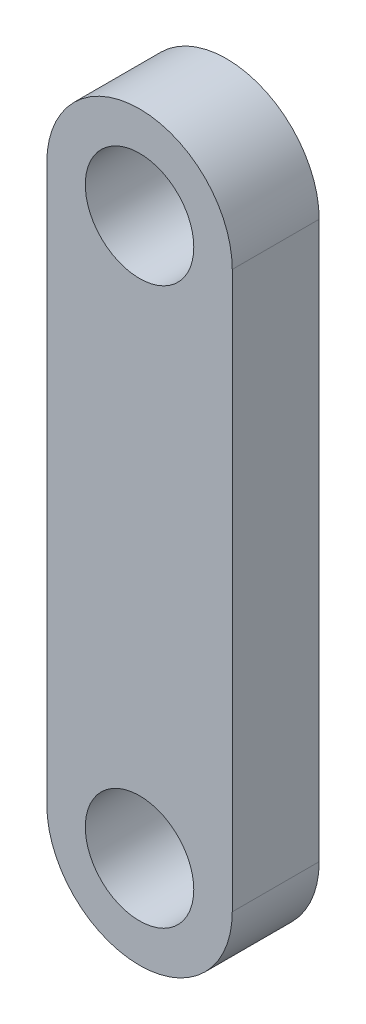
SolidWorks part; units mm, degrees
material "Titanium"
ref_plane "Front Plane" through (0, 0, 0) normal (0, 0, 1) x (1, 0, 0)
ref_plane "Top Plane" through (0, 0, 0) normal (0, 1, 0) x (1, 0, 0)
ref_plane "Right Plane" through (0, 0, 0) normal (1, 0, 0) x (0, 0, -1)
sketch "Sketch1" plane through (0, 0, 0) normal (0, 0, 1) x (1, 0, 0)
  line L3 (-3.2, 19.2) -> (-3.2, 0)
  line L4 (1.65, 0) -> (-1.65, 0) construction
  line L5 (3.2, 19.2) -> (3.2, 0)
  circle A2 centre (0, 0) radius 1.872
  circle A3 centre (0, 19.2) radius 1.872
  arc A4 (3.2, 19.2) -> (-3.2, 19.2) centre (0, 19.2) ccw
  arc A5 (-3.2, 0) -> (3.2, 0) centre (0, 0) ccw
  dimension "D1" = 6.4
  dimension "D2" = 3.744
  dimension "D3" = 19.2
extrude "Boss-Extrude1" add sketch "Sketch1" along normal blind 3
equation "\"bScale\"= 8"
equation "\"lScale\"= 8"
equation "\"D1@Sketch1\"=.8*\"bScale\""
equation "\"D2@Sketch1\"=0.468 * \"bScale\""
equation "\"D3@Sketch1\"=2.4*\"lScale\""
